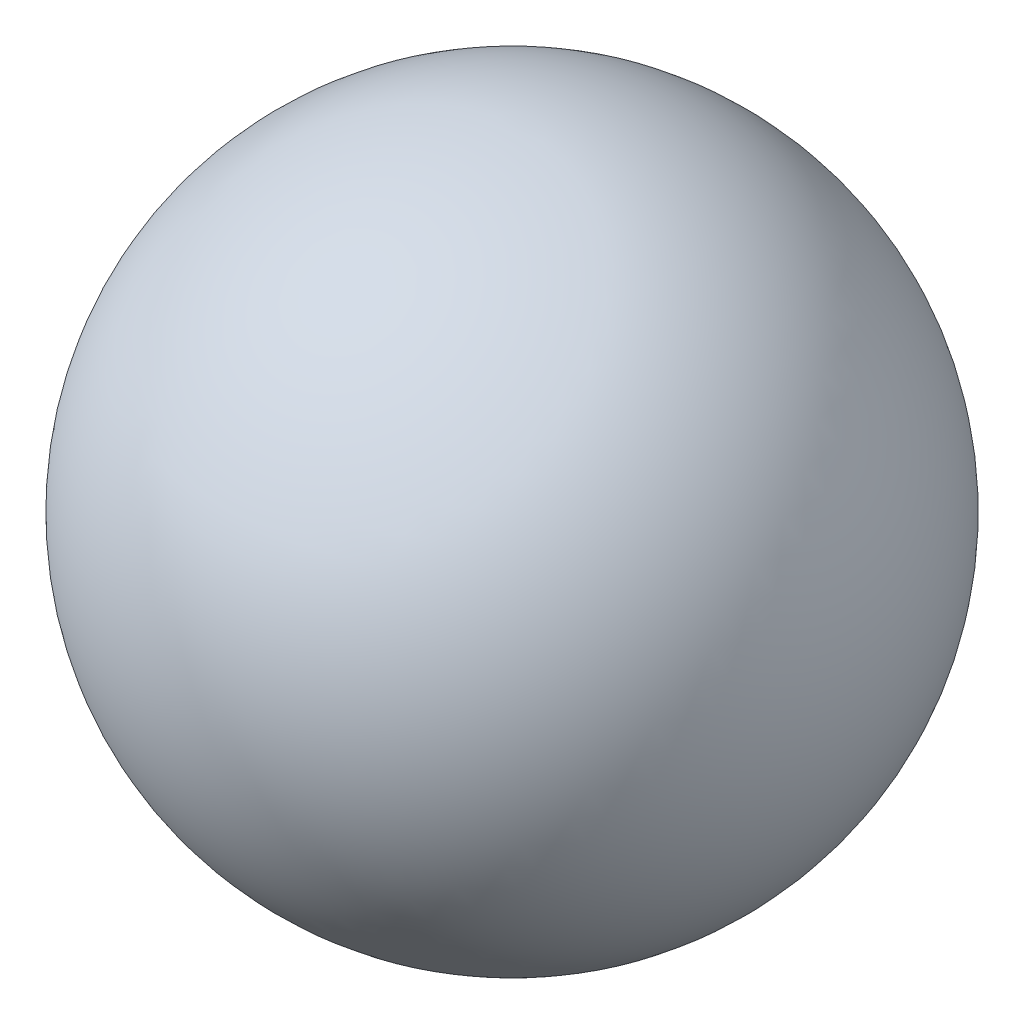
SolidWorks part; units mm, degrees
ref_plane "前视基准面" through (0, 0, 0) normal (0, 0, 1) x (1, 0, 0)
ref_plane "上视基准面" through (0, 0, 0) normal (0, 1, 0) x (1, 0, 0)
ref_plane "右视基准面" through (0, 0, 0) normal (1, 0, 0) x (0, 0, -1)
sketch "草图1" plane through (0, 0, 0) normal (0, 0, 1) x (1, 0, 0)
  line L0 (0, 8.5) -> (0, -8.5)
  arc A0 (0, 8.5) -> (0, -8.5) centre (0, 0) cw
  point P4 (3.2071, 7.8717)
  dimension "D1" = 8.5
revolve "旋转1" add sketch "草图1" angle 360 about L0
